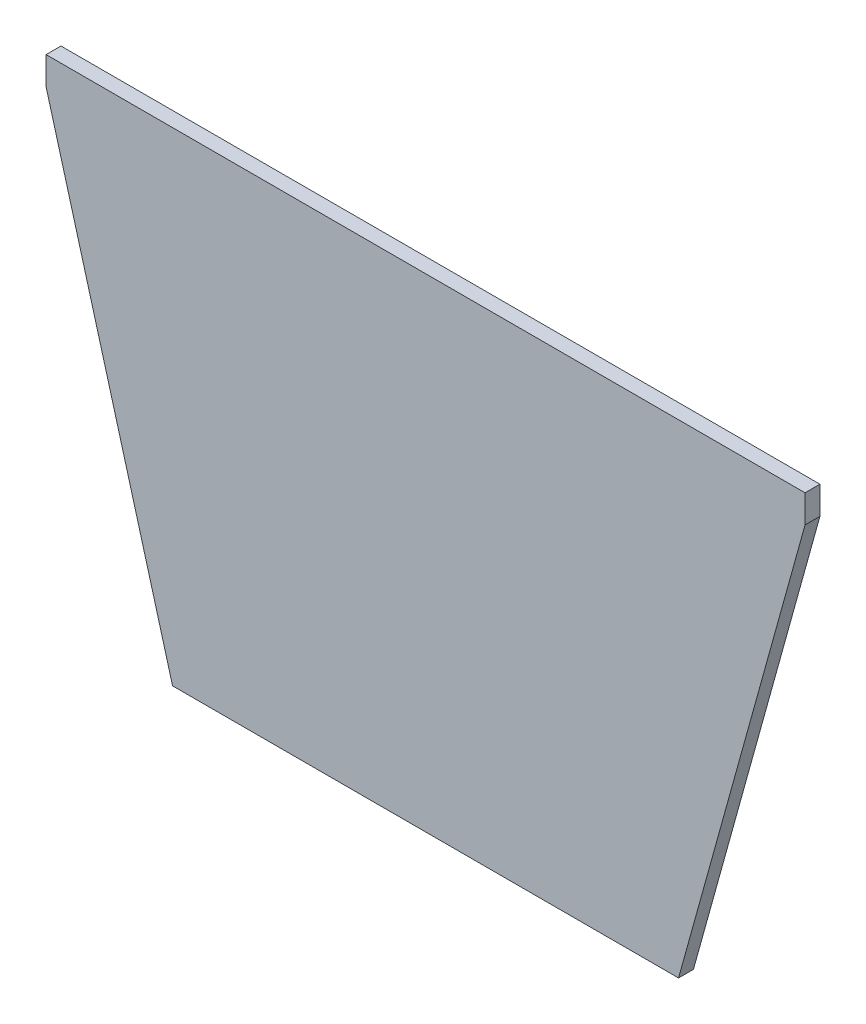
SolidWorks part; units mm, degrees
material "Thornel Mat VMA"
ref_plane "Płaszczyzna przednia" through (0, 0, 0) normal (0, 0, 1) x (1, 0, 0)
ref_plane "Płaszczyzna górna" through (0, 0, 0) normal (0, 1, 0) x (1, 0, 0)
ref_plane "Płaszczyzna prawa" through (0, 0, 0) normal (1, 0, 0) x (0, 0, -1)
sketch "Sketch1" plane through (0, 0, 0) normal (0, 0, 1) x (1, 0, 0)
  line L2 (33.991, 0) -> (169.971, 0)
  line L3 (203.962, 122.428) -> (169.971, 0)
  line L4 (101.981, 122.428) -> (101.981, -100.2438) construction
  line L5 (0, 122.428) -> (33.991, 0)
  line L6 (0, 122.428) -> (0, 129.928)
  line L8 (0, 129.928) -> (203.962, 129.928)
  line L9 (203.962, 129.928) -> (203.962, 122.428)
  point P0 (0, 0)
  point P1 (203.962, 0)
  point P9 (33.991, 0)
  dimension "D1" = 203.962
  dimension "D3" = 122.428
  dimension "D4" = 122.428
  dimension "D7" = 7.5
  dimension "D2" = 135.98
extrude "Boss-Extrude1" add sketch "Sketch1" along normal blind 4
